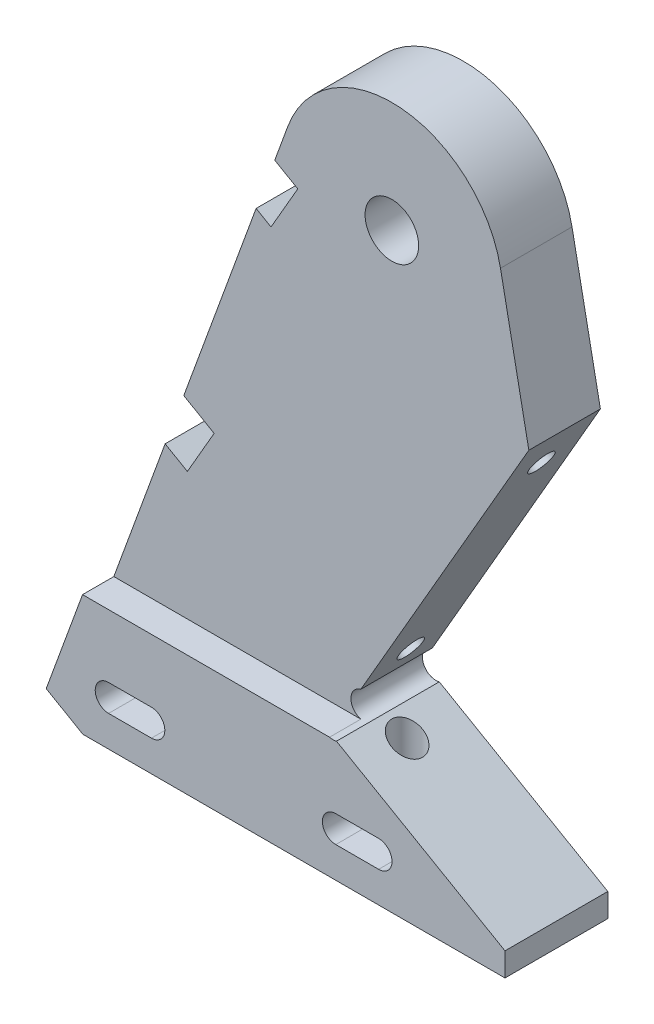
SolidWorks part; units mm, degrees
ref_plane "Front Plane" through (0, 0, 0) normal (0, 0, 1) x (1, 0, 0)
ref_plane "Top Plane" through (0, 0, 0) normal (0, 1, 0) x (1, 0, 0)
ref_plane "Right Plane" through (0, 0, 0) normal (1, 0, 0) x (0, 0, -1)
sketch "Model" plane through (0, 0, 0) normal (0, 0, 1) x (1, 0, 0)
  line L0 (30.032, -29.5212) -> (30.032, -26.7298)
  line L1 (-3.1895, 31.0479) -> (-11.7681, 7.5374)
  line L2 (12.4426, -6.5562) -> (9.2271, -12.1257) construction
  line L3 (16.6788, -19.0204) -> (10.0488, -15.1925) construction
  line L4 (9.6915, -11.3213) -> (10.8533, -15.657) construction
  line L5 (10.2724, -13.4891) -> (9.0035, -13.8291) construction
  line L6 (29.1519, 22.385) -> (9.2271, -12.1257)
  line L7 (30.032, -26.7298) -> (10.0488, -15.1925)
  line L8 (9.3745, -14.8032) -> (2.5284, -10.8506) construction
  line L9 (9.0235, -12.4784) -> (5.2305, -19.0481) construction
  line L10 (0.5709, 41.3535) -> (-0.9796, 37.1044)
  line L11 (0.0253, 32.858) -> (-15.4747, 6.0112) construction
  line L12 (-11.7681, 7.5374) -> (-8.1659, 5.4577)
  line L13 (-15.4747, 6.0112) -> (10.9052, -9.2192) construction
  line L14 (-11.7681, 7.5374) -> (-13.8872, 8.7609) construction
  line L15 (-11.3408, -0.0416) -> (-13.978, 1.4809) construction
  line L16 (-8.1659, 5.4577) -> (-11.3408, -0.0416)
  line L17 (-11.3408, -0.0416) -> (-13.978, 1.4809)
  line L18 (-13.978, 1.4809) -> (-24.3737, -27.0097)
  line L19 (0.0253, 32.858) -> (26.4052, 17.6276) construction
  line L20 (-1.4214, 30.0271) -> (1.7536, 35.5264)
  line L21 (-0.9796, 37.1044) -> (1.7536, 35.5264)
  line L22 (-3.1895, 31.0479) -> (-1.4214, 30.0271)
  line L23 (11.3113, 26.3421) -> (-4.1887, -0.5047) construction
  line L24 (3.5613, 12.9187) -> (-2.5691, 16.458) construction
  line L25 (12.2357, 35.6885) -> (0.2074, 14.855) construction
  line L26 (0.2074, 14.855) -> (12.9074, 36.8521) construction
  line L28 (29.1519, 22.385) -> (25.7905, 39.3975)
  line L80 (-20.0226, -29.5212) -> (-24.3737, -27.0097)
  line L82 (30.032, -29.5212) -> (-20.0226, -29.5212)
  circle A0 centre (12.9074, 36.8521) radius 3.175
  arc A2 (9.2271, -12.1257) -> (10.0488, -15.1925) centre (9.638, -13.6591) ccw
  arc A3 (25.7905, 39.3975) -> (0.5709, 41.3535) centre (12.9074, 36.8521) ccw
  point P11 (8.1045, -14.07)
  point P12 (8.1045, -14.07)
  point P37 (0.1661, 32.7767)
  dimension "D1" = 3.175
  dimension "D7" = 6.35
  dimension "D2" = 31
  dimension "D3" = 3.175
  dimension "D4" = 3.175
  dimension "D5" = 6.35
  dimension "D6" = 25.4
extrude "Boss-Extrude1" add sketch "Model" along normal blind 8.4836
sketch "Sketch2" plane through (0, 0, 8.4836) normal (0, 0, 1) x (1, 0, 0)
  line L0 (-32.0034, -15.1956) -> (9.2387, -15.1956) construction
  line L1 (-20.0226, -29.5212) -> (30.032, -29.5212) construction
  line L2 (-20.063, -15.1956) -> (9.2274, -15.1926)
  line L3 (-13.978, 1.4809) -> (-24.3737, -27.0097) construction
  line L4 (10.0488, -15.1925) -> (30.032, -26.7298)
  line L5 (30.032, -26.7298) -> (30.032, -29.5212)
  line L6 (30.032, -29.5212) -> (-20.0226, -29.5212)
  line L7 (-20.0226, -29.5212) -> (-24.3737, -27.0097)
  line L8 (-24.3737, -27.0097) -> (-20.063, -15.1956)
  line L9 (10.0372, -15.1956) -> (54.6863, -15.1956) construction
  line L10 (30.032, -29.5212) -> (30.032, -26.7298) construction
  arc A0 (9.2274, -15.1926) -> (10.0488, -15.1925) centre (9.638, -13.6591) ccw
  dimension "D1" = 14.3256
extrude "Boss-Extrude2" add sketch "Sketch2" along normal blind 3.7084
hole_wizard "#4 Clearance Hole3" positions "Sketch8" profile "Sketch9" hole size "#4" standard "ANSI Inch" end condition through all
sketch "Sketch8" plane through (-14.0682, 8.1223, 0) normal (-0.866, 0.5, 0) x (0, 0, 1)
  line L0 (8.4836, 25.2935) -> (0, 31.6435) construction
  point P7 (4.2418, 28.4685)
sketch "Sketch9" plane through (0.1661, 32.7767, 4.2418) normal (0, 0, 1) x (-0.5, -0.866, 0)
  line L0 (0, 0) -> (0, 57.0136)
  line L1 (0, 57.0136) -> (1.4732, 57.0136)
  line L2 (1.4732, 57.0136) -> (1.4732, 0)
  line L5 (1.4732, 0) -> (0, 0)
  line L11 (0, -6.35) -> (0, 107.95) construction
  dimension "Thru Hole Dia." = 2.9464
  dimension "Thru Hole Depth" = 57.0136
hole_wizard "#4 Clearance Hole4" positions "Sketch10" profile "Sketch11" hole size "#4" standard "ANSI Inch" end condition through all
sketch "Sketch10" plane through (-8.4878, 4.9001, 0) normal (-0.866, 0.5, 0) x (0, 0, 1)
  line L0 (0, 0.6438) -> (8.4836, -5.7062) construction
  point P7 (4.2418, -2.5312)
sketch "Sketch11" plane through (-9.7533, 2.708, 4.2418) normal (0, 0, 1) x (-0.5, -0.866, 0)
  line L0 (0, 0) -> (0, 50.5695)
  line L1 (0, 50.5695) -> (1.4732, 50.5695)
  line L2 (1.4732, 50.5695) -> (1.4732, 0)
  line L5 (1.4732, 0) -> (0, 0)
  line L11 (0, -6.35) -> (0, 107.95) construction
  dimension "Thru Hole Dia." = 2.9464
  dimension "Thru Hole Depth" = 50.5695
sketch "Sketch12" plane through (0, 0, 0) normal (0, 0, -1) x (-1, 0, 0)
  line L1 (-15.0462, -24.2634) -> (-9.9662, -24.2634) construction
  line L2 (-15.0462, -22.6759) -> (-9.9662, -22.6759)
  line L3 (-15.0462, -25.8509) -> (-9.9662, -25.8509)
  line L5 (11.8946, -24.2634) -> (16.9746, -24.2634) construction
  line L6 (11.8946, -22.6759) -> (16.9746, -22.6759)
  line L7 (11.8946, -25.8509) -> (16.9746, -25.8509)
  arc A0 (-15.0462, -22.6759) -> (-15.0462, -25.8509) centre (-15.0462, -24.2634) ccw
  arc A1 (-9.9662, -25.8509) -> (-9.9662, -22.6759) centre (-9.9662, -24.2634) ccw
  arc A2 (11.8946, -22.6759) -> (11.8946, -25.8509) centre (11.8946, -24.2634) ccw
  arc A3 (16.9746, -25.8509) -> (16.9746, -22.6759) centre (16.9746, -24.2634) ccw
  point P6 (-12.5062, -24.2634)
  point P18 (14.4346, -24.2634)
  dimension "D1" = 1.5875
  dimension "D2" = 1.5875
  dimension "D3" = 14.9858
extrude "Cut-Extrude1" cut sketch "Sketch12" against normal through all
hole_wizard "#6 Clearance Hole1" positions "Sketch13" profile "Sketch14" hole size "#6" standard "ANSI Inch"
sketch "Sketch13" plane through (0, -29.5212, 0) normal (0, -1, 0) x (-1, 0, 0)
  point P0 (14.4338, -6.2714)
  point P3 (-12.5069, -6.2714)
sketch "Sketch14" plane through (-14.4338, -29.5212, 6.2714) normal (1, 0, 0) x (0, 0, -1)
  line L0 (0, 0) -> (0, 15.425)
  line L1 (0, 15.425) -> (1.8288, 14.3262)
  line L2 (1.8288, 14.3262) -> (1.8288, 0)
  line L5 (1.8288, 0) -> (0, 0)
  line L10 (0, 15.425) -> (-1.8288, 14.3262) construction
  line L11 (0, -6.35) -> (0, 107.95) construction
  dimension "Hole Dia." = 3.6576
  dimension "Hole Depth" = 14.3262
  dimension "Drill Angle" = 118
